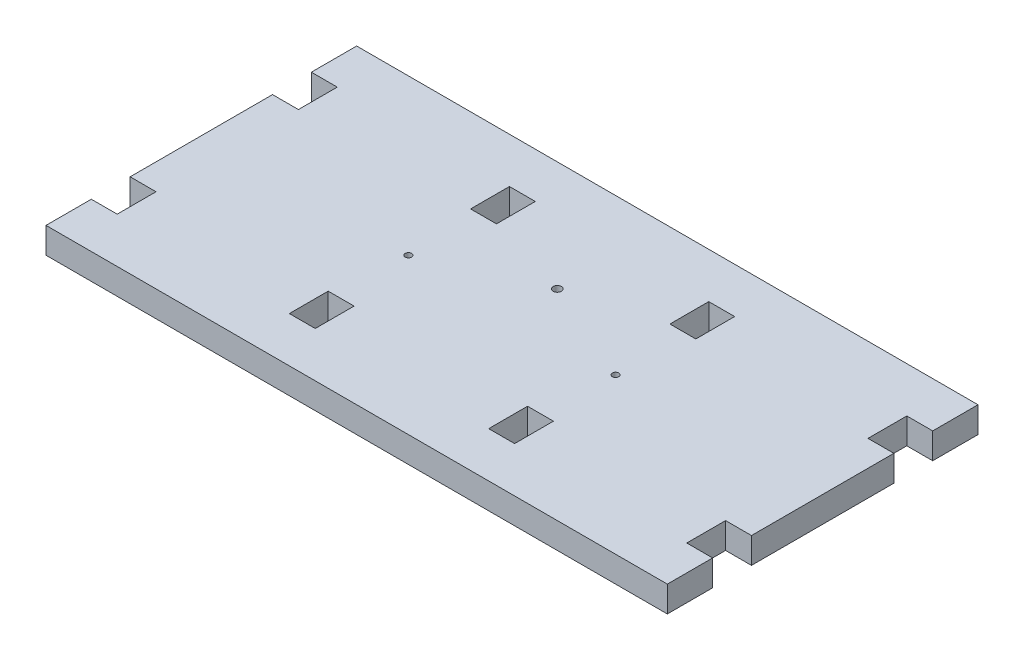
SolidWorks part; units mm, degrees
material "Acrylic (Medium-high impact)"
ref_plane "Front Plane" through (0, 0, 0) normal (0, 0, 1) x (1, 0, 0)
ref_plane "Top Plane" through (0, 0, 0) normal (0, 1, 0) x (1, 0, 0)
ref_plane "Right Plane" through (0, 0, 0) normal (1, 0, 0) x (0, 0, -1)
sketch "Sketch1" plane through (0, 0, 0) normal (0, 1, 0) x (1, 0, 0)
  line L1 (-152.4, 76.2) -> (152.4, 76.2)
  line L2 (-152.4, 76.2) -> (-152.4, -76.2)
  line L3 (-152.4, -76.2) -> (152.4, -76.2)
  line L4 (152.4, 76.2) -> (152.4, -76.2)
  line L5 (-152.4, 76.2) -> (152.4, -76.2) construction
  line L6 (-152.4, -76.2) -> (152.4, 76.2) construction
  point P0 (0, 0)
extrude "Extrude1" add sketch "Sketch1" along normal blind 12.7
sketch "Sketch2" plane through (0, 12.7, 0) normal (0, 1, 0) x (1, 0, 0)
  line L0 (0, 0) -> (0, 93.8784) construction
  line L1 (0, 0) -> (156.2405, 0) construction
  line L2 (-55.245, 53.975) -> (-55.245, 34.925)
  line L3 (42.545, 53.975) -> (55.245, 53.975)
  line L4 (42.545, 53.975) -> (42.545, 34.925)
  line L5 (42.545, 34.925) -> (55.245, 34.925)
  line L6 (55.245, 53.975) -> (55.245, 34.925)
  line L7 (-42.545, 34.925) -> (-55.245, 34.925)
  line L8 (-42.545, 53.975) -> (-42.545, 34.925)
  line L9 (-42.545, 53.975) -> (-55.245, 53.975)
  line L10 (-42.545, -53.975) -> (-55.245, -53.975)
  line L11 (-42.545, -53.975) -> (-42.545, -34.925)
  line L12 (-42.545, -34.925) -> (-55.245, -34.925)
  line L13 (55.245, -53.975) -> (55.245, -34.925)
  line L14 (42.545, -34.925) -> (55.245, -34.925)
  line L15 (42.545, -53.975) -> (42.545, -34.925)
  line L16 (42.545, -53.975) -> (55.245, -53.975)
  line L17 (-55.245, -53.975) -> (-55.245, -34.925)
  line L18 (152.4, -76.2) -> (152.4, 76.2) construction
  line L19 (152.4, 53.975) -> (139.7, 53.975)
  line L20 (152.4, 53.975) -> (152.4, 34.925)
  line L21 (152.4, 34.925) -> (139.7, 34.925)
  line L22 (139.7, 53.975) -> (139.7, 34.925)
  line L23 (-139.7, 53.975) -> (-139.7, 34.925)
  line L24 (-152.4, 34.925) -> (-139.7, 34.925)
  line L25 (-152.4, 53.975) -> (-152.4, 34.925)
  line L26 (-152.4, 53.975) -> (-139.7, 53.975)
  line L27 (139.7, -53.975) -> (139.7, -34.925)
  line L28 (152.4, -34.925) -> (139.7, -34.925)
  line L29 (152.4, -53.975) -> (152.4, -34.925)
  line L30 (152.4, -53.975) -> (139.7, -53.975)
  line L31 (-152.4, -53.975) -> (-139.7, -53.975)
  line L32 (-152.4, -53.975) -> (-152.4, -34.925)
  line L33 (-152.4, -34.925) -> (-139.7, -34.925)
  line L34 (-139.7, -53.975) -> (-139.7, -34.925)
  dimension "D1" = 19.05
  dimension "D2" = 12.7
  dimension "D3" = 42.545
  dimension "D4" = 34.925
extrude "Extrude2" cut sketch "Sketch2" against normal through all
sketch "Sketch3" plane through (0, 0, 0) normal (0, -1, 0) x (1, 0, 0)
  circle A0 centre (50.8, 0) radius 1.5875
  circle A1 centre (-50.8, 0) radius 1.5875
  dimension "D1" = 3.175
extrude "Cut-Extrude1" cut sketch "Sketch3" against normal through all
sketch "Sketch4" plane through (0, 12.7, 0) normal (0, 1, 0) x (1, 0, 0)
  circle A0 centre (0, 22.225) radius 2.032 construction
  circle A1 centre (0, 22.225) radius 2.032
extrude "Cut-Extrude2" cut sketch "Sketch4" against normal through all
